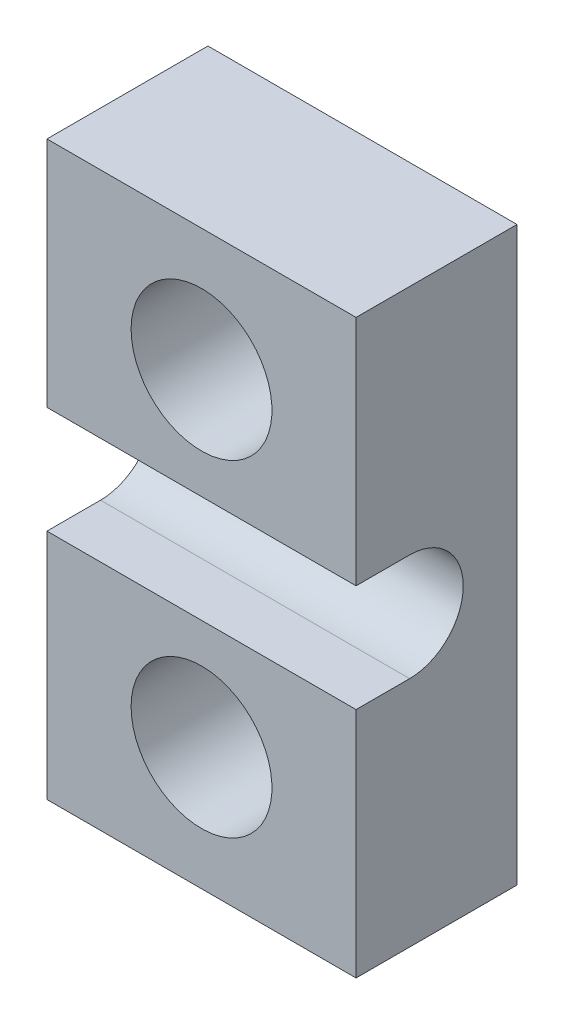
SolidWorks part; units mm, degrees
ref_plane "Front Plane" through (0, 0, 0) normal (0, 0, 1) x (1, 0, 0)
ref_plane "Top Plane" through (0, 0, 0) normal (0, 1, 0) x (1, 0, 0)
ref_plane "Right Plane" through (0, 0, 0) normal (1, 0, 0) x (0, 0, -1)
sketch "Sketch1" plane through (0, 0, 0) normal (0, 0, 1) x (1, 0, 0)
  line L1 (216.551, 143.9246) -> (210.4061, 143.9246)
  line L2 (216.551, 143.9246) -> (216.551, 132.5512)
  line L3 (216.551, 132.5512) -> (210.4061, 132.5512)
  line L4 (210.4061, 143.9246) -> (210.4061, 132.5512)
extrude "Boss-Extrude1" add sketch "Sketch1" along normal blind 3.2
sketch "Sketch2" plane through (0, 0, 0) normal (0, 0, -1) x (-1, 0, 0)
  line L0 (-213.4785, 141.4879) -> (-213.4785, 134.9879) construction
  line L1 (-213.4785, 141.4879) -> (-213.4785, 143.9246) construction
  line L2 (-216.551, 143.9246) -> (-210.4061, 143.9246) construction
  line L3 (-213.4785, 134.9879) -> (-213.4785, 132.5512) construction
  line L4 (-210.4061, 132.5512) -> (-216.551, 132.5512) construction
  circle A0 centre (-213.4785, 141.4879) radius 1.4
  circle A1 centre (-213.4785, 134.9879) radius 1.4
  dimension "D1" = 2.8
  dimension "D2" = 6.5
extrude "Cut-Extrude1" cut sketch "Sketch2" against normal through all
sketch "Sketch3" plane through (216.551, 0, 0) normal (1, 0, 0) x (0, 0, -1)
  line L0 (-3.2, 138.2379) -> (0, 138.2379) construction
  line L1 (-3.2, 132.5512) -> (-3.2, 143.9246) construction
  line L2 (-2.135, 137.1729) -> (-3.2, 137.1729)
  line L3 (0, 132.5512) -> (0, 143.9246) construction
  line L4 (-2.135, 139.3029) -> (-3.2, 139.3029)
  line L5 (-3.2, 137.1729) -> (-3.2, 139.3029)
  arc A0 (-2.135, 137.1729) -> (-2.135, 139.3029) centre (-2.135, 138.2379) ccw
  dimension "D1" = 2.13
extrude "Cut-Extrude2" cut sketch "Sketch3" against normal through all
